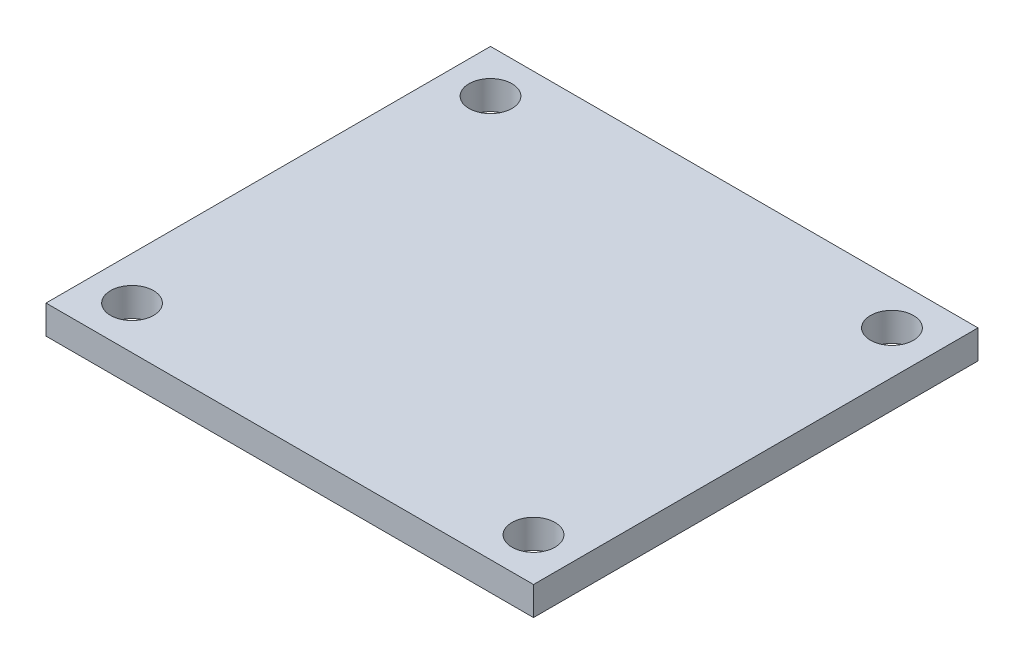
SolidWorks part; units mm, degrees
ref_plane "Front Plane" through (0, 0, 0) normal (0, 0, 1) x (1, 0, 0)
ref_plane "Top Plane" through (0, 0, 0) normal (0, 1, 0) x (1, 0, 0)
ref_plane "Right Plane" through (0, 0, 0) normal (1, 0, 0) x (0, 0, -1)
sketch "Sketch1" plane through (0, 0, 0) normal (0, 1, 0) x (1, 0, 0)
  line L0 (17, 31) -> (17, 0) construction
  line L1 (0, 0) -> (34, 0)
  line L2 (0, 0) -> (0, 31)
  line L3 (0, 31) -> (34, 31)
  line L4 (34, 0) -> (34, 31)
  line L6 (0, 15.5) -> (34, 15.5) construction
  circle A0 centre (3, 28) radius 1.5
  circle A1 centre (31, 28) radius 1.5
  circle A2 centre (31, 3) radius 1.5
  circle A3 centre (3, 3) radius 1.5
  dimension "D3" = 3
  dimension "D4" = 3
  dimension "D5" = 3
  dimension "D1" = 31
  dimension "D2" = 34
extrude "Boss-Extrude1" add sketch "Sketch1" along normal blind 2
